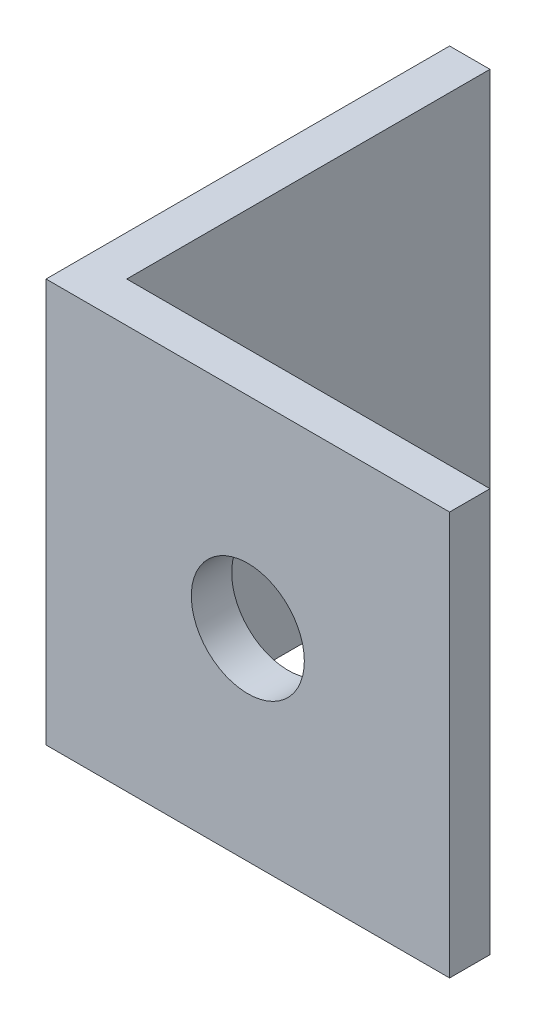
SolidWorks part; units mm, degrees
ref_plane "前视基准面" through (0, 0, 0) normal (0, 0, 1) x (1, 0, 0)
ref_plane "上视基准面" through (0, 0, 0) normal (0, 1, 0) x (1, 0, 0)
ref_plane "右视基准面" through (0, 0, 0) normal (1, 0, 0) x (0, 0, -1)
sketch "草图1" plane through (0, 0, 0) normal (0, 0, 1) x (1, 0, 0)
  line L0 (-25, 0) -> (25, 0) construction
  line L1 (-25, -25) -> (25, -25)
  line L2 (-25, -25) -> (-25, 25)
  line L3 (-25, 25) -> (25, 25)
  line L4 (25, -25) -> (25, 25)
  line L5 (-25, -25) -> (25, 25) construction
  line L6 (-25, 25) -> (25, -25) construction
  circle A0 centre (0, 0) radius 7
  point P0 (0, 0)
  point P10 (0, 0)
  dimension "D3" = 14
  dimension "D1" = 50
  dimension "D2" = 50
extrude "凸台-拉伸1" add sketch "草图1" along normal blind 5
sketch "草图2" plane through (-25, 0, 0) normal (-1, 0, 0) x (0, 0, 1)
  line L0 (5, -25) -> (0, -25) construction
  line L1 (5, 25) -> (-45, 25)
  line L2 (5, 25) -> (5, -25)
  line L3 (5, -25) -> (-45, -25)
  line L4 (-45, 25) -> (-45, -25)
  point P5 (5, -25)
  dimension "D1" = 50
extrude "凸台-拉伸2" add sketch "草图2" against normal blind 5
